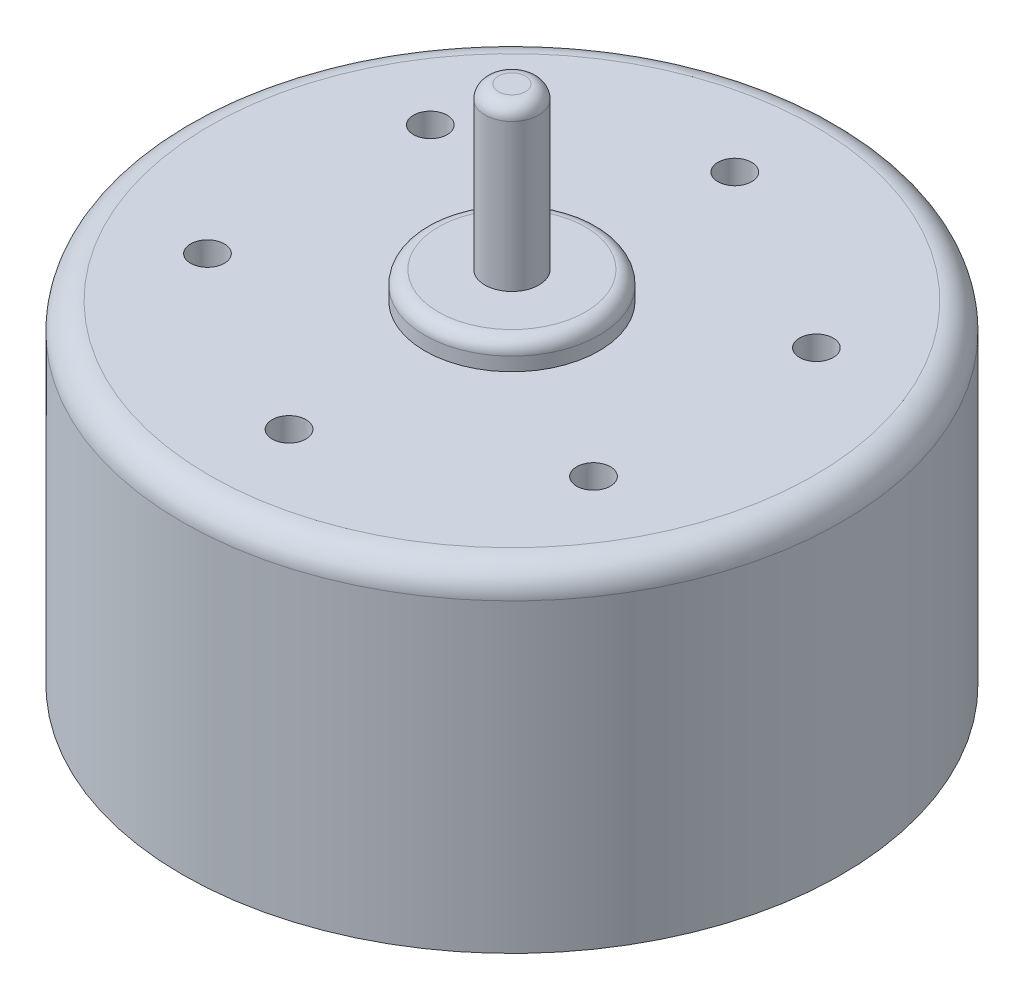
SolidWorks part; units mm, degrees
ref_plane "Front Plane" through (0, 0, 0) normal (0, 0, 1) x (1, 0, 0)
ref_plane "Top Plane" through (0, 0, 0) normal (0, 1, 0) x (1, 0, 0)
ref_plane "Right Plane" through (0, 0, 0) normal (1, 0, 0) x (0, 0, -1)
sketch "Sketch1" plane through (0, 0, 0) normal (0, 1, 0) x (1, 0, 0)
  circle A0 centre (0, 0) radius 12.2
  dimension "D1" = 24.4
extrude "Boss-Extrude1" add sketch "Sketch1" along normal blind 12.3
sketch "Sketch2" plane through (0, 12.3, 0) normal (0, 1, 0) x (1, 0, 0)
  circle A0 centre (0, 0) radius 3.225
  dimension "D1" = 6.45
extrude "Boss-Extrude2" add sketch "Sketch2" along normal blind 1
sketch "Sketch3" plane through (0, 0, 0) normal (0, -1, 0) x (1, 0, 0)
  circle A0 centre (0, 0) radius 3.05
  dimension "D1" = 6.1
extrude "Boss-Extrude3" add sketch "Sketch3" along normal blind 0.5
sketch "Sketch4" plane through (0, 13.3, 0) normal (0, 1, 0) x (1, 0, 0)
  circle A0 centre (0, 0) radius 1
  dimension "D1" = 2
extrude "Boss-Extrude4" add sketch "Sketch4" along normal blind 5.95
fillet "Fillet1" radius 1 1 edges at (0, 12.3, 12.2)
fillet "Fillet2" radius 0.5 2 edges at (0, 13.3, 3.225) (0, 19.25, 1)
hole_wizard "Tap Drill for M1.6x0.35 Tap1" positions "Sketch6" profile "Sketch7" hole size "M1.6x0.35" standard "JIS"
sketch "Sketch6" plane through (0, 12.3, 0) normal (0, 1, 0) x (1, 0, 0)
  circle A0 centre (0, 0) radius 8.25
  point P0 (0, -8.25)
  point P14 (-7.1447, -4.125)
  point P15 (-7.1447, 4.125)
  point P16 (0, 8.25)
  point P17 (7.1447, 4.125)
  point P18 (7.1447, -4.125)
  dimension "D1" = 16.5
  dimension "D2" = 6
sketch "Sketch7" plane through (0, 12.3, 8.25) normal (1, 0, 0) x (0, 0, 1)
  line L0 (0, 0) -> (0, 1.4755)
  line L1 (0, 1.4755) -> (0.625, 1.1)
  line L2 (0.625, 1.1) -> (0.625, 0)
  line L5 (0.625, 0) -> (0, 0)
  line L10 (0, 1.4755) -> (-0.625, 1.1) construction
  line L11 (0, -6.35) -> (0, 107.95) construction
  dimension "Hole Dia." = 1.25
  dimension "Hole Depth" = 1.1
  dimension "Drill Angle" = 118
sketch "Sketch8" plane through (0, 0, 0) normal (0, -1, 0) x (1, 0, 0)
  circle A0 centre (0, 0) radius 3.05
  circle A1 centre (0, 0) radius 3.05 construction
  circle A2 centre (0, 0) radius 11.7
  circle A3 centre (0, 0) radius 12.2 construction
  dimension "D1" = 0.5
extrude "Cut-Extrude1" cut sketch "Sketch8" against normal blind 0.5
